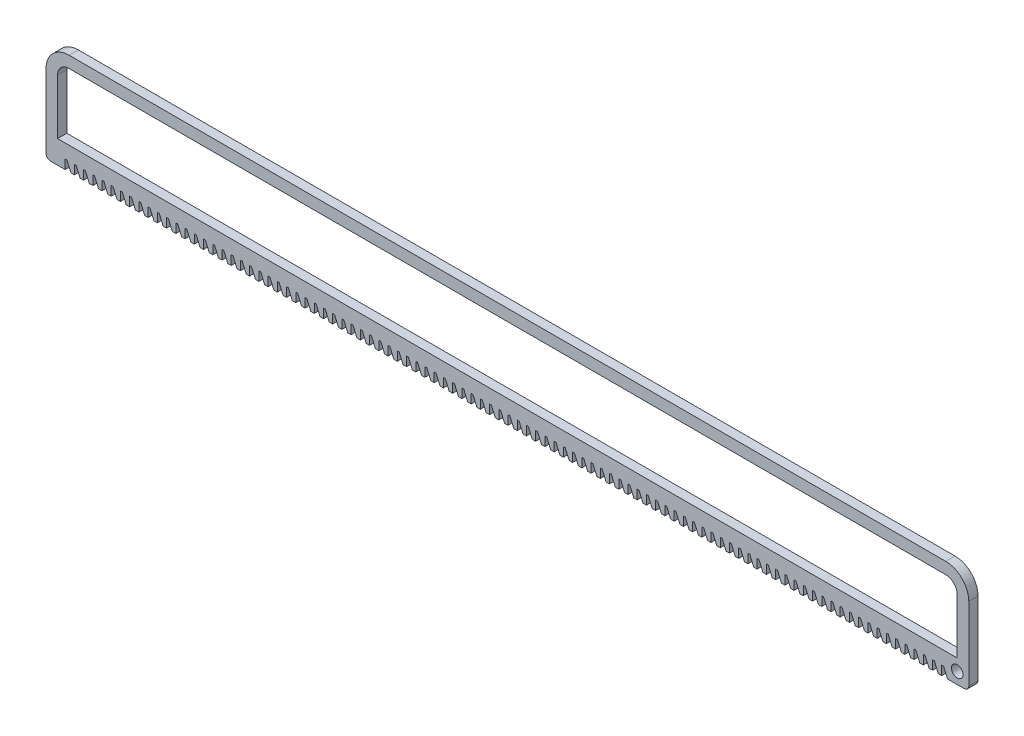
SolidWorks part; units mm, degrees
ref_plane "Front" through (0, 0, 0) normal (0, 0, 1) x (1, 0, 0)
ref_plane "Top" through (0, 0, 0) normal (0, 1, 0) x (1, 0, 0)
ref_plane "Right" through (0, 0, 0) normal (1, 0, 0) x (0, 0, -1)
sketch "Sketch1" plane through (0, 0, 0) normal (0, 0, 1) x (1, 0, 0)
  line L1 (-200, -5) -> (200, -5)
  line L2 (-200, -5) -> (-200, 5)
  line L3 (-200, 5) -> (200, 5)
  line L4 (200, -5) -> (200, 5)
  line L5 (-200, -5) -> (200, 5) construction
  line L6 (-200, 5) -> (200, -5) construction
  point P0 (0, 0)
  dimension "D1" = 400
  dimension "D2" = 10
extrude "Boss-Extrude1" add sketch "Sketch1" along normal blind 4
sketch "Sketch2" plane through (0, 0, 0) normal (0, 0, 1) x (1, 0, 0)
  line L0 (-200, 5) -> (-200, 28.7939)
  line L1 (-190, 38.7939) -> (190, 38.7939)
  line L2 (200, 28.7939) -> (200, 5)
  line L3 (-195, 5) -> (-195, 28.7939)
  line L4 (-190, 33.7939) -> (190, 33.7939)
  line L5 (195, 28.7939) -> (195, 5)
  line L6 (-200, 5) -> (-195, 5)
  line L7 (195, 5) -> (200, 5)
  arc A0 (190, 38.7939) -> (200, 28.7939) centre (190, 28.7939) cw
  arc A1 (-190, 38.7939) -> (-200, 28.7939) centre (-190, 28.7939) ccw
  arc A2 (-190, 33.7939) -> (-195, 28.7939) centre (-190, 28.7939) ccw
  arc A3 (190, 33.7939) -> (195, 28.7939) centre (190, 28.7939) cw
  dimension "D1" = 10
  dimension "D2" = 5
extrude "Boss-Extrude2" add sketch "Sketch2" along normal up to surface (4 mm away) up to face at (0, 0, 4)
sketch "Sketch4" plane through (0, 0, 4) normal (0, 0, 1) x (1, 0, 0)
  line L0 (-195, 5) -> (-195, -5)
  line L1 (-200, -5) -> (200, -5) construction
  line L2 (-143.7176, -1) -> (-143.7176, -5)
  line L4 (-143.7176, -1) -> (-142.9176, -1)
  line L5 (-142.9176, -1) -> (-141.2176, -5)
  line L6 (-141.2176, -5) -> (-143.7176, -5)
  line L9 (195, 5) -> (195, -5)
  line L10 (195, 0) -> (144.1316, 0) construction
  line M19 (-200, -5) -> (200, -5)
  dimension "D1" = 4
  dimension "D2" = 0.8
  dimension "D3" = 2.5
extrude "Cut-Extrude13" cut sketch "Sketch4" against normal through all contours L5 L4 L2 M19
pattern_linear "LPattern2" count 84 spacing 4 along (1, 0, 0) count 13 spacing 4 along (-1, 0, 0) of "Cut-Extrude13"
sketch "Sketch5" plane through (0, 0, 4) normal (0, 0, 1) x (1, 0, 0)
  line L0 (200, -5) -> (200, 0)
  line L1 (200, -5) -> (200, 28.7939) construction
  line L2 (200, 0) -> (195, 0)
  circle A0 centre (195, 0) radius 2.5
  dimension "D2" = 5
  dimension "D1" = 5
extrude "Cut-Extrude14" cut sketch "Sketch5" against normal through all contours A0
fillet "Fillet7" radius 2 2 edges at (200, -5, 2) (-200, -5, 2)
